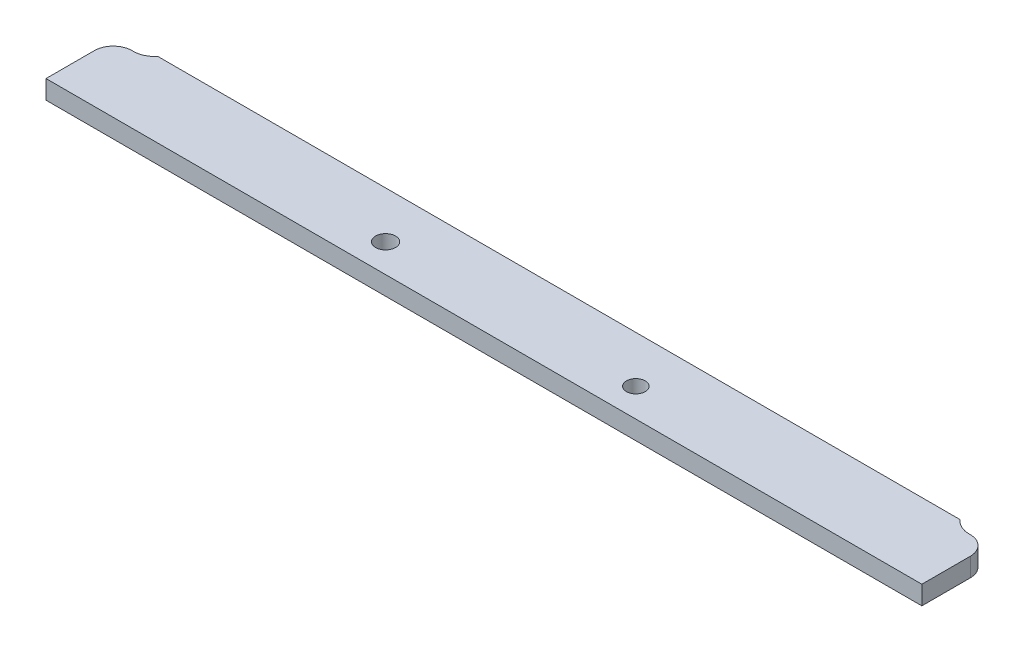
SolidWorks part; units mm, degrees
ref_plane "Front Plane" through (0, 0, 0) normal (0, 0, 1) x (1, 0, 0)
ref_plane "Top Plane" through (0, 0, 0) normal (0, 1, 0) x (1, 0, 0)
ref_plane "Right Plane" through (0, 0, 0) normal (1, 0, 0) x (0, 0, -1)
sketch "Sketch3" plane through (0, 0, 0) normal (0, 1, 0) x (1, 0, 0)
  line L6 (125.4903, 26.3608) -> (-2.7409, 26.3608)
  line L7 (-5.431, 25.0999) -> (-5.6253, 25.0999)
  line L8 (-8.6253, 22.0999) -> (-8.6253, 14.3589)
  line L9 (-8.6253, 14.3589) -> (131.3747, 14.3589)
  line L10 (131.3747, 14.3589) -> (131.3747, 22.0999)
  line L11 (128.3747, 25.0999) -> (128.1804, 25.0999)
  line L12 (125.4903, 26.3608) -> (-2.7409, 26.3608)
  line L13 (-5.431, 25.0999) -> (-5.6253, 25.0999)
  line L14 (-8.6253, 22.0999) -> (-8.6253, 14.3589)
  line L15 (-8.6253, 14.3589) -> (131.3747, 14.3589)
  line L16 (131.3747, 14.3589) -> (131.3747, 22.0999)
  line L17 (128.3747, 25.0999) -> (128.1804, 25.0999)
  arc A4 (125.4903, 26.3608) -> (128.1804, 25.0999) centre (128.1804, 28.5999) ccw
  arc A5 (-5.431, 25.0999) -> (-2.7409, 26.3608) centre (-5.431, 28.5999) ccw
  arc A6 (-5.6253, 25.0999) -> (-8.6253, 22.0999) centre (-5.6253, 22.0999) ccw
  arc A7 (131.3747, 22.0999) -> (128.3747, 25.0999) centre (128.3747, 22.0999) ccw
  arc A8 (125.4903, 26.3608) -> (128.1804, 25.0999) centre (128.1804, 28.5999) ccw
  arc A9 (-5.431, 25.0999) -> (-2.7409, 26.3608) centre (-5.431, 28.5999) ccw
  arc A10 (-5.6253, 25.0999) -> (-8.6253, 22.0999) centre (-5.6253, 22.0999) ccw
  arc A11 (131.3747, 22.0999) -> (128.3747, 25.0999) centre (128.3747, 22.0999) ccw
  dimension "D1" = 0
extrude "Boss-Extrude1" add sketch "Sketch3" along normal blind 3
sketch "Sketch4" plane through (0, 3, 0) normal (0, 1, 0) x (1, 0, 0)
  arc A0 (41.1098, 20.5031) -> (41.1098, 17.3031) centre (41.1098, 18.9031) ccw construction
  arc A1 (41.1098, 17.3031) -> (41.1098, 20.5031) centre (41.1098, 18.9031) ccw construction
  circle A2 centre (81.1098, 18.9031) radius 1.5 construction
  arc A3 (41.1098, 20.5031) -> (41.1098, 17.3031) centre (41.1098, 18.9031) ccw
  arc A4 (41.1098, 17.3031) -> (41.1098, 20.5031) centre (41.1098, 18.9031) ccw
  circle A5 centre (81.1098, 18.9031) radius 1.5
extrude "Cut-Extrude1" cut sketch "Sketch4" against normal up to next
